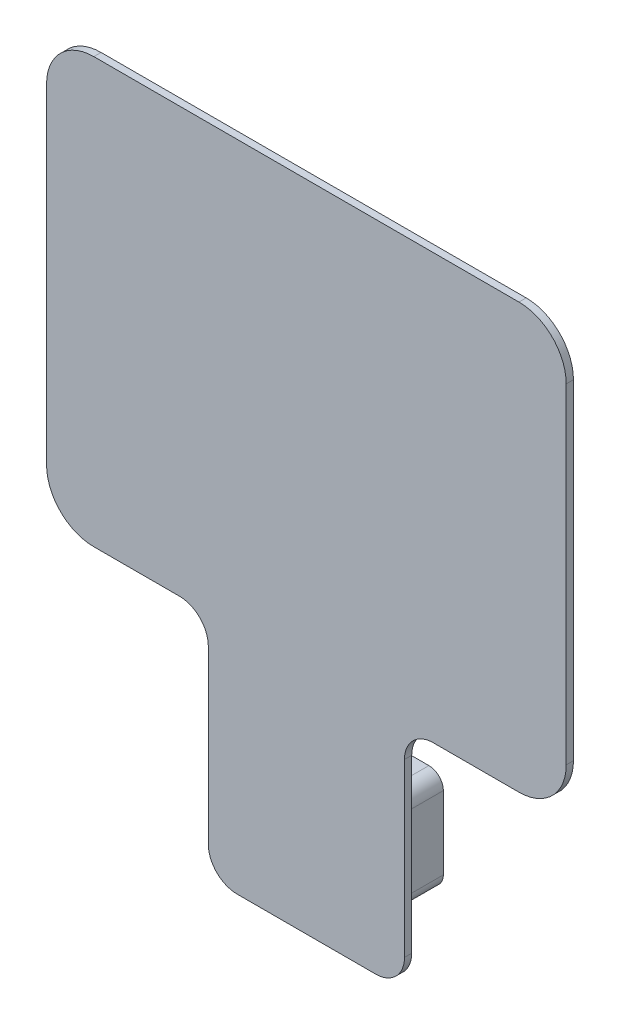
SolidWorks part; units mm, degrees
ref_plane "Front Plane" through (0, 0, 0) normal (0, 0, 1) x (1, 0, 0)
ref_plane "Top Plane" through (0, 0, 0) normal (0, 1, 0) x (1, 0, 0)
ref_plane "Right Plane" through (0, 0, 0) normal (1, 0, 0) x (0, 0, -1)
sketch "Sketch1" plane through (0, 0, 0) normal (0, 0, 1) x (1, 0, 0)
  line L0 (-147.1846, 293.942) -> (147.1846, 293.942)
  line L1 (-179.919, 261.2076) -> (-179.919, 32.7344)
  line L2 (-147.1846, 0) -> (-87.9221, 0)
  line L3 (179.919, 261.2076) -> (179.919, 32.7344)
  line L4 (87.9221, 0) -> (147.1846, 0)
  line L5 (-67.9221, -20) -> (-67.9221, -138.6901)
  line L6 (-47.9221, -158.6901) -> (47.9221, -158.6901)
  line L7 (67.9221, -20) -> (67.9221, -138.6901)
  line L8 (-67.9221, 158.6901) -> (67.9221, -158.6901) construction
  line L9 (-67.9221, -158.6901) -> (67.9221, 158.6901) construction
  arc A0 (-147.1846, 293.942) -> (-179.919, 261.2076) centre (-147.1846, 261.2076) ccw
  arc A1 (179.919, 261.2076) -> (147.1846, 293.942) centre (147.1846, 261.2076) ccw
  arc A2 (-179.919, 32.7344) -> (-147.1846, 0) centre (-147.1846, 32.7344) ccw
  arc A3 (147.1846, 0) -> (179.919, 32.7344) centre (147.1846, 32.7344) ccw
  arc A4 (67.9221, -138.6901) -> (47.9221, -158.6901) centre (47.9221, -138.6901) cw
  arc A5 (-47.9221, -158.6901) -> (-67.9221, -138.6901) centre (-47.9221, -138.6901) cw
  arc A6 (87.9221, 0) -> (67.9221, -20) centre (87.9221, -20) ccw
  arc A7 (-67.9221, -20) -> (-87.9221, 0) centre (-87.9221, -20) ccw
  point P1 (0, 0)
  dimension "D1" = 20
extrude "Boss-Extrude1" add sketch "Sketch1" along normal blind 5
sketch "Sketch2" plane through (0, 0, 5) normal (0, 0, 1) x (1, 0, 0)
  circle A0 centre (-147.1846, 261.2076) radius 9
  circle A1 centre (147.1846, 261.2076) radius 9
  circle A2 centre (147.1846, 32.7344) radius 9
  circle A3 centre (-147.1846, 32.7344) radius 9
  dimension "D1" = 18
extrude "Cut-Extrude1" cut sketch "Sketch2" against normal blind 75
sketch "Sketch3" plane through (0, 0, 5) normal (0, 0, 1) x (1, 0, 0)
  line L0 (139.5828, 272.9537) -> (133.2112, 260.4973)
  line L1 (-140.813, 273.664) -> (-154.7864, 272.9537)
  line L2 (-154.7864, 272.9537) -> (-161.158, 260.4973)
  line L3 (-161.158, 260.4973) -> (-153.5561, 248.7511)
  line L4 (-153.5561, 248.7511) -> (-139.5828, 249.4614)
  line L5 (-139.5828, 249.4614) -> (-133.2112, 261.9178)
  line L6 (-133.2112, 261.9178) -> (-140.813, 273.664)
  line L7 (153.5561, 273.664) -> (139.5828, 272.9537)
  line L8 (133.2112, 260.4973) -> (140.813, 248.7511)
  line L9 (140.813, 248.7511) -> (154.7864, 249.4614)
  line L10 (161.158, 261.9178) -> (153.5561, 273.664)
  line L11 (154.7864, 249.4614) -> (161.158, 261.9178)
  line L12 (139.5828, 44.4806) -> (133.2112, 32.0241)
  line L13 (153.5561, 45.1909) -> (139.5828, 44.4806)
  line L14 (133.2112, 32.0241) -> (140.813, 20.278)
  line L15 (140.813, 20.278) -> (154.7864, 20.9883)
  line L16 (161.158, 33.4447) -> (153.5561, 45.1909)
  line L17 (154.7864, 20.9883) -> (161.158, 33.4447)
  line L18 (-154.7864, 44.4806) -> (-161.158, 32.0241)
  line L19 (-140.813, 45.1909) -> (-154.7864, 44.4806)
  line L20 (-161.158, 32.0241) -> (-153.5561, 20.278)
  line L21 (-153.5561, 20.278) -> (-139.5828, 20.9883)
  line L22 (-133.2112, 33.4447) -> (-140.813, 45.1909)
  line L23 (-139.5828, 20.9883) -> (-133.2112, 33.4447)
  circle A0 centre (-147.1846, 261.2076) radius 12.1169 construction
  circle A1 centre (147.1846, 261.2076) radius 12.1169 construction
  circle A2 centre (147.1846, 32.7344) radius 12.1169 construction
  circle A3 centre (-147.1846, 32.7344) radius 12.1169 construction
extrude "Boss-Extrude2" add sketch "Sketch3" against normal blind 15
sketch "Sketch4" plane through (0, 0, -10) normal (0, 0, -1) x (-1, 0, 0)
  circle A0 centre (-147.1846, 261.2076) radius 11.6839
  circle A1 centre (-147.1846, 261.2076) radius 18.1162
  circle A2 centre (-147.1846, 32.7344) radius 18.1162
  circle A3 centre (-147.1846, 32.7344) radius 11.6839
  circle A4 centre (147.1846, 32.7344) radius 18.1162
  circle A5 centre (147.1846, 32.7344) radius 11.6839
  circle A6 centre (147.1846, 261.2076) radius 18.1162
  circle A7 centre (147.1846, 261.2076) radius 11.6839
extrude "Cut-Extrude2" cut sketch "Sketch4" against normal blind 15 draft 45
sketch "Sketch5" plane through (0, 0, 0) normal (0, 0, -1) x (-1, 0, 0)
  line L1 (-49.8209, -60.2126) -> (51.1125, -60.2126)
  line L2 (-49.8209, -60.2126) -> (-49.8209, -130.7579)
  line L3 (-49.8209, -130.7579) -> (51.1125, -130.7579)
  line L4 (51.1125, -60.2126) -> (51.1125, -130.7579)
extrude "Boss-Extrude3" add sketch "Sketch5" along normal blind 40
fillet "Fillet1" radius 10 4 edges at (-51.1125, -130.7579, -20) (-51.1125, -60.2126, -20) (49.8209, -130.7579, -20) (49.8209, -60.2126, -20)
sketch "Sketch6" plane through (0, 0, -40) normal (0, 0, -1) x (-1, 0, 0)
  line L1 (-39.8209, -70.2126) -> (41.1125, -70.2126)
  line L2 (-39.8209, -70.2126) -> (-39.8209, -120.7579)
  line L3 (-39.8209, -120.7579) -> (41.1125, -120.7579)
  line L4 (41.1125, -70.2126) -> (41.1125, -120.7579)
extrude "Cut-Extrude3" cut sketch "Sketch6" against normal blind 7
sketch "Sketch7" plane through (0, 0, -33) normal (0, 0, -1) x (-1, 0, 0)
  circle A0 centre (-24.147, -82.3825) radius 6.4053
  circle A1 centre (0.6458, -82.3825) radius 6.4053
  circle A2 centre (0.6458, -103.3788) radius 6.4053
  circle A3 centre (25.493, -82.3825) radius 6.4053
extrude "Cut-Extrude4" cut sketch "Sketch7" against normal blind 22
